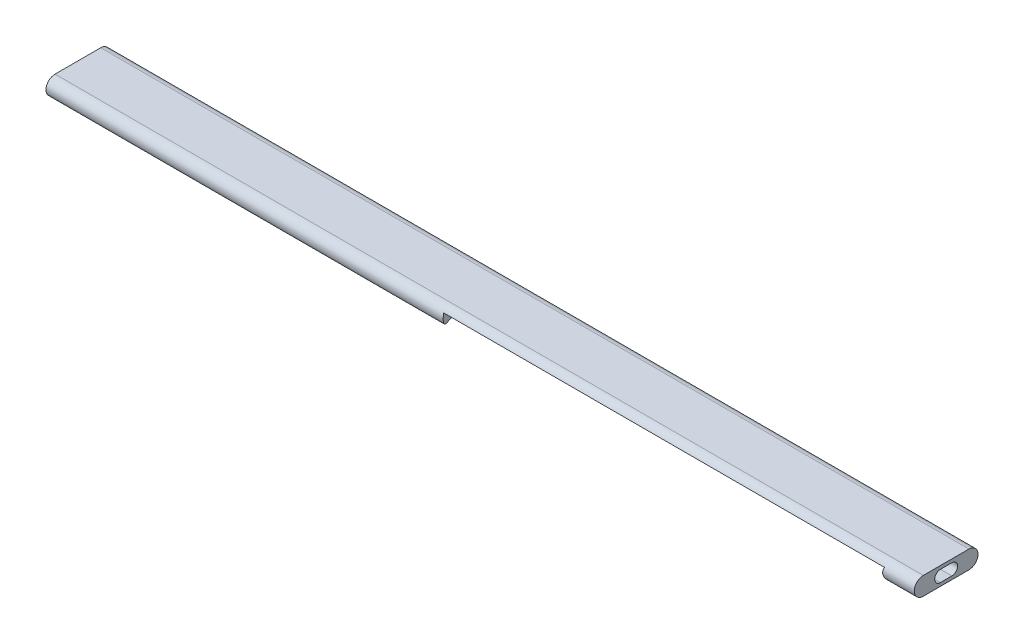
SolidWorks part; units mm, degrees
ref_plane "前视基准面" through (0, 0, 0) normal (0, 0, 1) x (1, 0, 0)
ref_plane "上视基准面" through (0, 0, 0) normal (0, 1, 0) x (1, 0, 0)
ref_plane "右视基准面" through (0, 0, 0) normal (1, 0, 0) x (0, 0, -1)
sketch "草图2" plane through (0, 0, 0) normal (1, 0, 0) x (0, 0, -1)
  line L0 (-10, 0) -> (10, 0) construction
  line L1 (-10, 3.95) -> (10, 3.95)
  line L2 (-10, -3.95) -> (10, -3.95)
  arc A0 (-10, 3.95) -> (-10, -3.95) centre (-10, 0) ccw
  arc A1 (10, -3.95) -> (10, 3.95) centre (10, 0) ccw
  point P2 (0, 0)
  point P8 (13.95, 0)
  point P9 (-13.95, 0)
  dimension "D1" = 27.9
  dimension "D2" = 7.9
extrude "凸台-拉伸1" add sketch "草图2" along normal blind 380
sketch "草图3" plane through (0, 0, 0) normal (-1, 0, 0) x (0, 0, 1)
  line L0 (2.5, 0) -> (-2.5, 0) construction
  line L1 (2.5, -2.5) -> (-2.5, -2.5)
  line L2 (2.5, 2.5) -> (-2.5, 2.5)
  arc A0 (2.5, -2.5) -> (2.5, 2.5) centre (2.5, 0) ccw
  arc A1 (-2.5, 2.5) -> (-2.5, -2.5) centre (-2.5, 0) ccw
  point P2 (0, 0)
  point P8 (-5, 0)
  point P9 (5, 0)
  dimension "D1" = 10
  dimension "D2" = 5
extrude "切除-拉伸1" cut sketch "草图3" against normal blind 390
sketch "草图5" plane through (0, -3.95, 0) normal (0, -1, 0) x (1, 0, 0)
  line L0 (197.2788, 0) -> (342.7212, 0) construction
  line L1 (197.2788, 27.2788) -> (342.7212, 27.2788)
  line L2 (197.2788, -27.2788) -> (342.7212, -27.2788)
  line L4 (380, 10) -> (380, -10) construction
  arc A0 (197.2788, 27.2788) -> (197.2788, -27.2788) centre (197.2788, 0) ccw
  arc A1 (342.7212, -27.2788) -> (342.7212, 27.2788) centre (342.7212, 0) ccw
  point P2 (270, 0)
  point P8 (370, 0)
  point P9 (170, 0)
  point P10 (277.0734, 0)
  point P11 (266.779, 0)
  dimension "D2" = 10
  dimension "D1" = 200
extrude "切除-拉伸2" cut sketch "草图5" against normal offset from surface (5.9 mm away) 2 up to face at (190, 3.95, 0)
